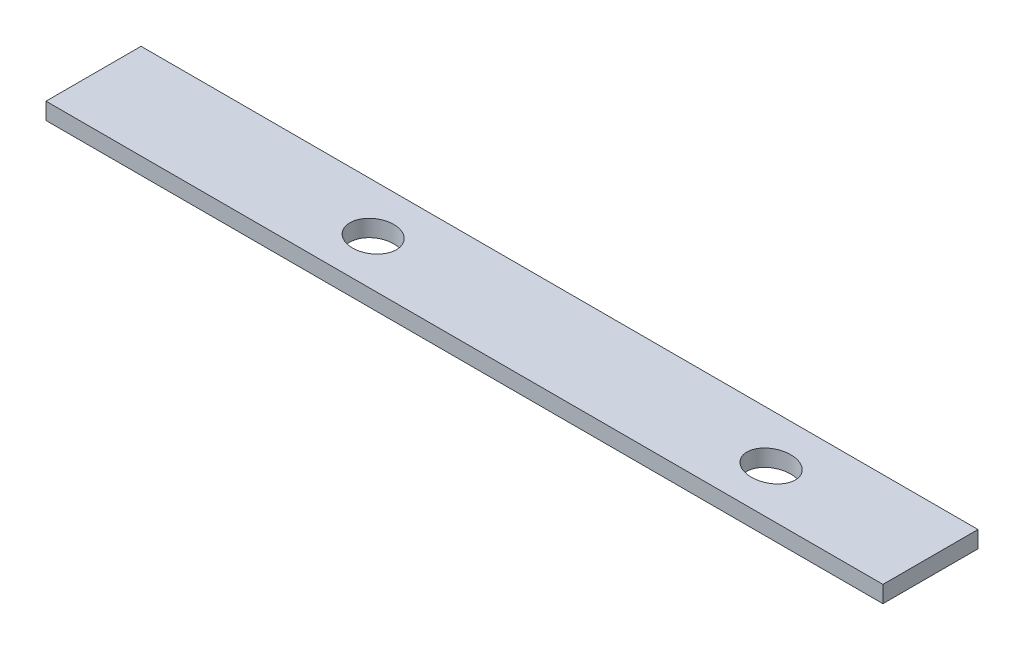
SolidWorks part; units mm, degrees
ref_plane "Front Plane" through (0, 0, 0) normal (0, 0, 1) x (1, 0, 0)
ref_plane "Top Plane" through (0, 0, 0) normal (0, 1, 0) x (1, 0, 0)
ref_plane "Right Plane" through (0, 0, 0) normal (1, 0, 0) x (0, 0, -1)
sketch "Sketch1" plane through (0, 0, 0) normal (0, 1, 0) x (1, 0, 0)
  line L1 (-25.4358, 0) -> (19.4642, 0)
  line L2 (-25.4358, 0) -> (-25.4358, -5.1)
  line L3 (-25.4358, -5.1) -> (19.4642, -5.1)
  line L4 (19.4642, 0) -> (19.4642, -5.1)
  dimension "D1" = 5.1
  dimension "D2" = 44.9
extrude "Boss-Extrude2" add sketch "Sketch1" along normal blind 0.9
sketch "Sketch3" plane through (0, 0.9, 0) normal (0, 1, 0) x (1, 0, 0)
  line L0 (-25.4358, 0) -> (-25.4358, -5.1) construction
  line L1 (19.4642, -2.6) -> (10.9642, -2.6)
  line L2 (19.4642, -5.1) -> (19.4642, 0) construction
  line L3 (-10.3858, 3.5046) -> (-10.3858, -9.9266)
  line L4 (-25.4358, -2.6) -> (10.9642, -2.6)
  line L5 (19.4642, 0) -> (-25.4358, 0) construction
  line L6 (10.9642, -2.6) -> (10.9642, 1.3273)
  line L7 (10.9642, -2.6) -> (10.9642, -7.5472)
  ellipse E0 centre (-10.3858, -2.6) end of major axis (-9.1358, -2.6) minor radius 1.1
  ellipse E1 centre (10.9642, -2.6) end of major axis (9.6642, -2.6) minor radius 1.05
  dimension "D1" = 2.2
  dimension "D2" = 2.5
  dimension "D3" = 1.5
  dimension "D4" = 13.8
  dimension "D5" = 7.2
  dimension "D6" = 2.1
  dimension "D7" = 2.6
extrude "Cut-Extrude4" cut sketch "Sketch3" against normal blind 0.9 contours E1 | E0
sketch "Sketch6" plane through (19.4642, 0, 0) normal (1, 0, 0) x (0, 0, -1)
  line L0 (-5.1, 0.9) -> (0, 0.9) construction
  circle A0 centre (-4.0146, 0.9) radius 0.005
  dimension "D1" = 0.01
